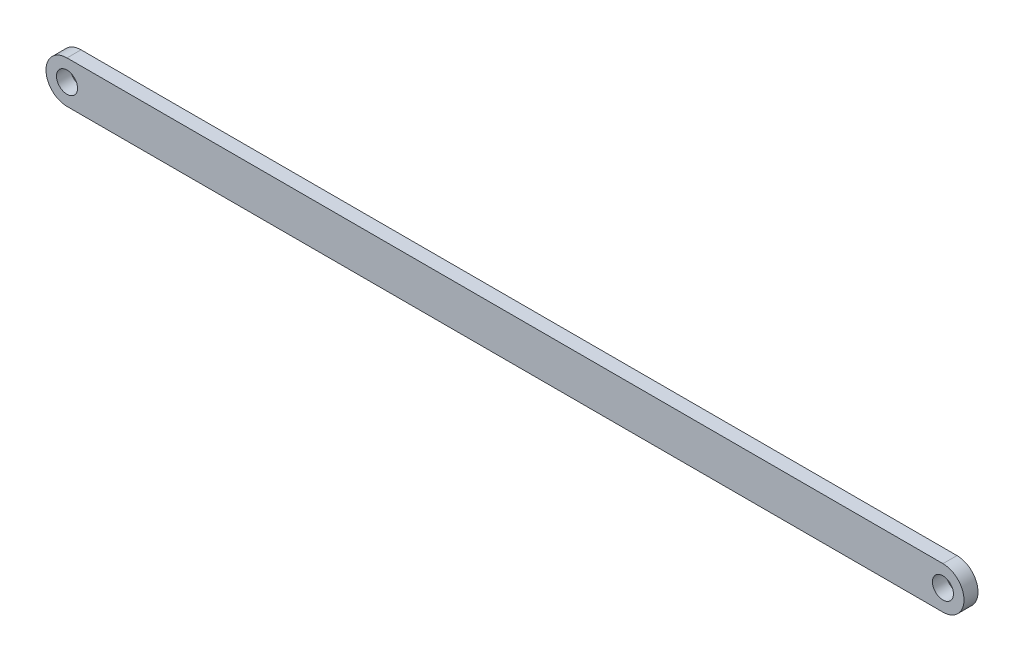
SolidWorks part; units mm, degrees
ref_plane "正面" through (0, 0, 0) normal (0, 0, 1) x (1, 0, 0)
ref_plane "平面" through (0, 0, 0) normal (0, 1, 0) x (1, 0, 0)
ref_plane "右側面" through (0, 0, 0) normal (1, 0, 0) x (0, 0, -1)
sketch "ｽｹｯﾁ1" plane through (0, 0, 0) normal (0, 0, 1) x (1, 0, 0)
  line L0 (0, 0) -> (250, 0) construction
  line L1 (0, 6) -> (250, 6)
  line L2 (0, -6) -> (250, -6)
  arc A0 (0, 6) -> (0, -6) centre (0, 0) ccw
  arc A1 (250, -6) -> (250, 6) centre (250, 0) ccw
  circle A2 centre (0, 0) radius 3
  circle A3 centre (250, 0) radius 3
  point P3 (125, 0)
  dimension "D1" = 6
  dimension "D3" = 6
  dimension "D2" = 250
extrude "ﾎﾞｽ - 押し出し1" add sketch "ｽｹｯﾁ1" along normal blind 4
